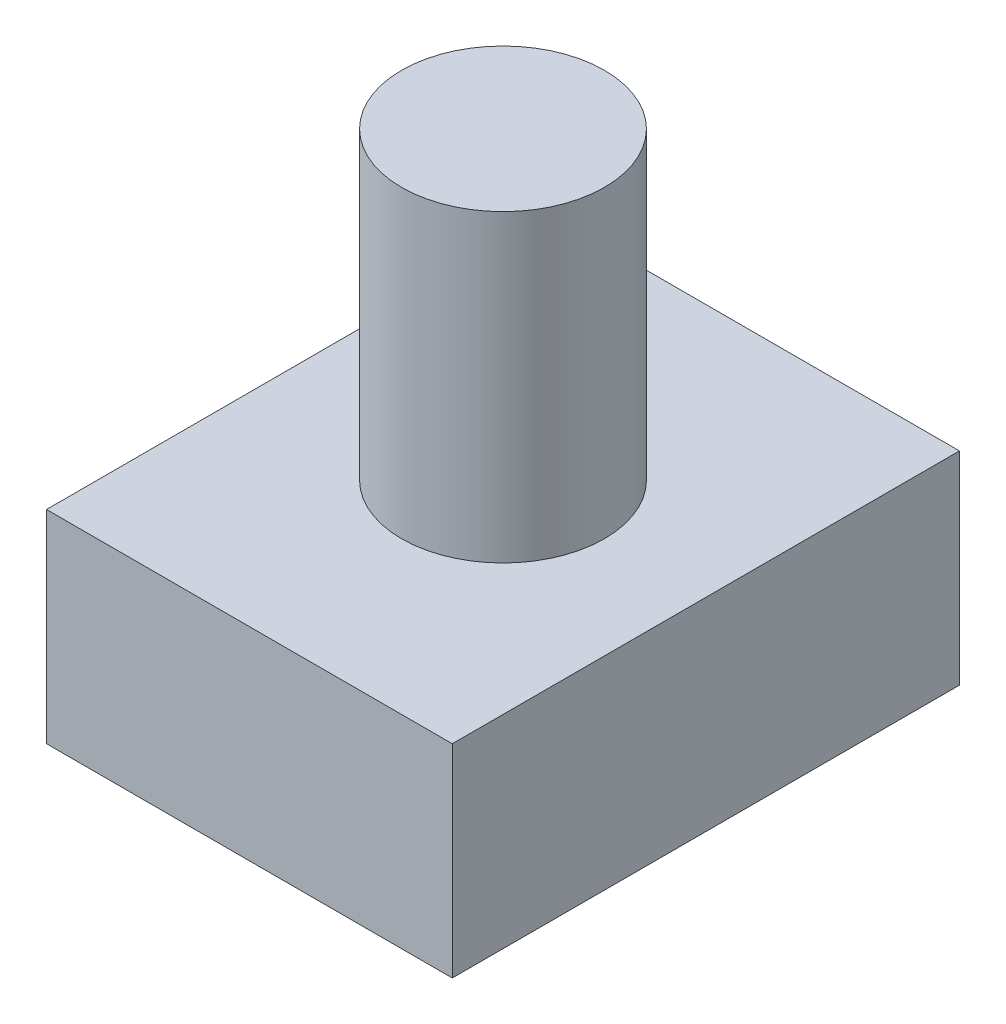
SolidWorks part; units mm, degrees
ref_plane "Front Plane" through (0, 0, 0) normal (0, 0, 1) x (1, 0, 0)
ref_plane "Top Plane" through (0, 0, 0) normal (0, 1, 0) x (1, 0, 0)
ref_plane "Right Plane" through (0, 0, 0) normal (1, 0, 0) x (0, 0, -1)
sketch "Sketch1" plane through (0, 0, 0) normal (0, 1, 0) x (1, 0, 0)
  line L1 (0, 0) -> (40, 0)
  line L2 (0, 0) -> (0, 50)
  line L3 (0, 50) -> (40, 50)
  line L4 (40, 0) -> (40, 50)
  dimension "D1" = 40
  dimension "D2" = 50
extrude "Boss-Extrude1" add sketch "Sketch1" along normal blind 20
sketch "Sketch2" plane through (0, 20, 0) normal (0, 1, 0) x (1, 0, 0)
  line L0 (20, 50) -> (20, 0) construction
  line L1 (40, 50) -> (0, 50) construction
  line L2 (0, 0) -> (40, 0) construction
  circle A0 centre (20, 25) radius 10
  dimension "D1" = 20
extrude "Boss-Extrude2" add sketch "Sketch2" along normal blind 30
